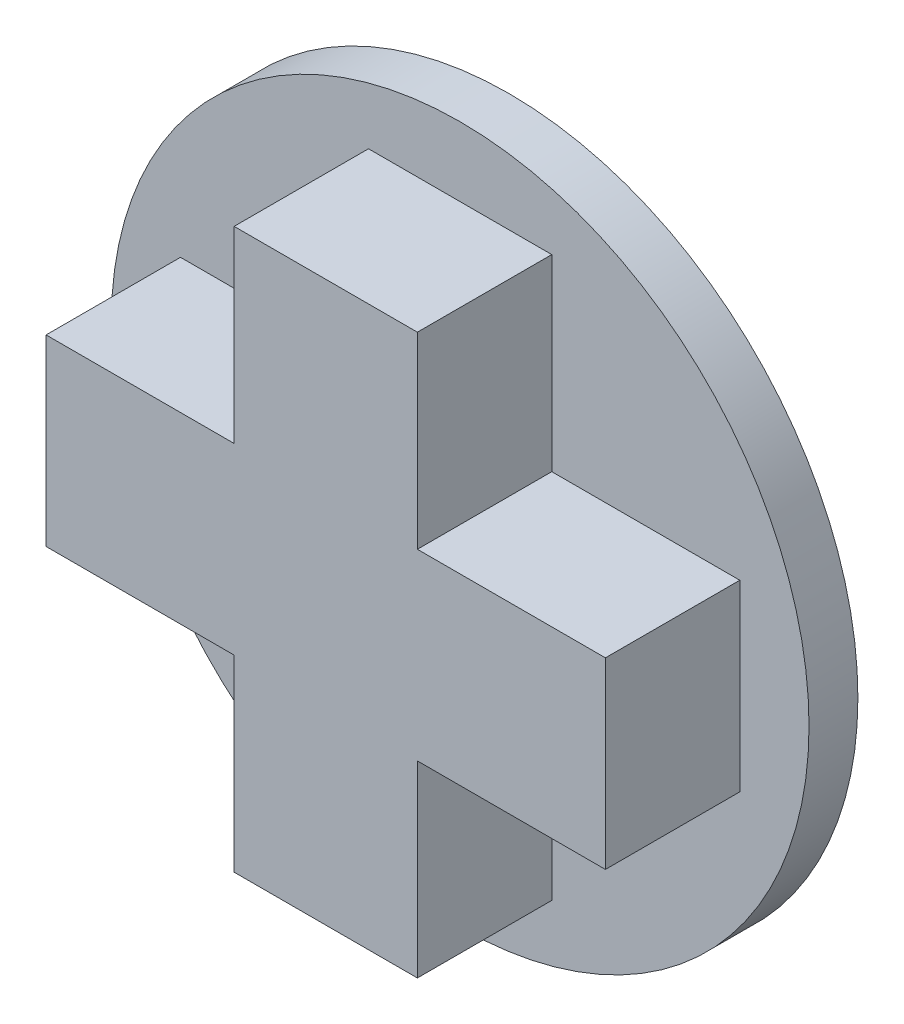
SolidWorks part; units mm, degrees
ref_plane "Front Plane" through (0, 0, 0) normal (0, 0, 1) x (1, 0, 0)
ref_plane "Top Plane" through (0, 0, 0) normal (0, 1, 0) x (1, 0, 0)
ref_plane "Right Plane" through (0, 0, 0) normal (1, 0, 0) x (0, 0, -1)
sketch "Sketch1" plane through (0, 0, 0) normal (0, 0, 1) x (1, 0, 0)
  circle A0 centre (0, 0) radius 12.85
  dimension "D1" = 25.7
extrude "Boss-Extrude1" add sketch "Sketch1" along normal blind 1.8
sketch "Sketch2" plane through (0, 0, 1.8) normal (0, 0, 1) x (1, 0, 0)
  line L0 (3.375, 3.375) -> (10.3, 3.375)
  line L1 (-3.375, -10.3) -> (3.375, -10.3)
  line L2 (-3.375, -10.3) -> (-3.375, -3.375)
  line L3 (-3.375, 10.3) -> (3.375, 10.3)
  line L4 (3.375, -10.3) -> (3.375, -3.375)
  line L5 (-3.375, 10.3) -> (3.375, -10.3) construction
  line L6 (-3.375, -10.3) -> (3.375, 10.3) construction
  line L7 (-10.3, -3.375) -> (-3.375, -3.375)
  line L8 (-10.3, -3.375) -> (-10.3, 3.375)
  line L9 (-10.3, 3.375) -> (-3.375, 3.375)
  line L10 (10.3, -3.375) -> (10.3, 3.375)
  line L11 (10.3, 3.375) -> (-10.3, -3.375) construction
  line L12 (-10.3, 3.375) -> (10.3, -3.375) construction
  line L14 (3.375, 3.375) -> (3.375, 10.3)
  line L16 (3.375, -3.375) -> (10.3, -3.375)
  line L19 (-3.375, 3.375) -> (-3.375, 10.3)
  point P0 (0, 0)
  point P6 (0, 0)
  dimension "D1" = 20.6
  dimension "D2" = 20.6
  dimension "D3" = 6.75
extrude "Boss-Extrude2" add sketch "Sketch2" along normal blind 4.95
sketch "Sketch3" plane through (0, 0, 0) normal (0, 0, -1) x (-1, 0, 0)
  circle A0 centre (0, 0) radius 2.65
  dimension "D1" = 5.3
extrude "Boss-Extrude3" add sketch "Sketch3" along normal blind 2.5
fillet "Fillet1" radius 1.25 1 edges at (-2.65, 0, -2.5)
